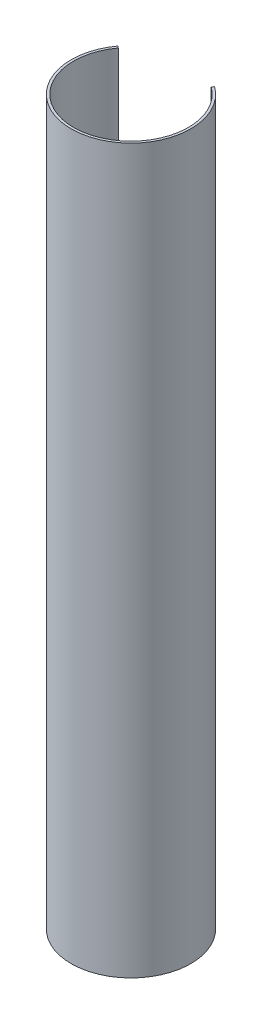
SolidWorks part; units mm, degrees
ref_plane "Front Plane" through (0, 0, 0) normal (0, 0, 1) x (1, 0, 0)
ref_plane "Top Plane" through (0, 0, 0) normal (0, 1, 0) x (1, 0, 0)
ref_plane "Right Plane" through (0, 0, 0) normal (1, 0, 0) x (0, 0, -1)
sketch "Sketch2" plane through (0, 0, 0) normal (0, 1, 0) x (1, 0, 0)
  line L0 (-125, 0) -> (125, 0)
  line L1 (-101.1121, 73.4938) -> (0, 0)
  line L2 (0, 0) -> (73.4938, 101.1121)
  circle A0 centre (0, 0) radius 120
  circle A1 centre (0, 0) radius 125
  dimension "D1" = 240
  dimension "D2" = 250
  dimension "D3" = 90
extrude "Boss-Extrude1" add sketch "Sketch2" along normal blind 1510 contours L0 A1 L2 A0 | L1 A1 L0 A0 | L0 A1 A0
